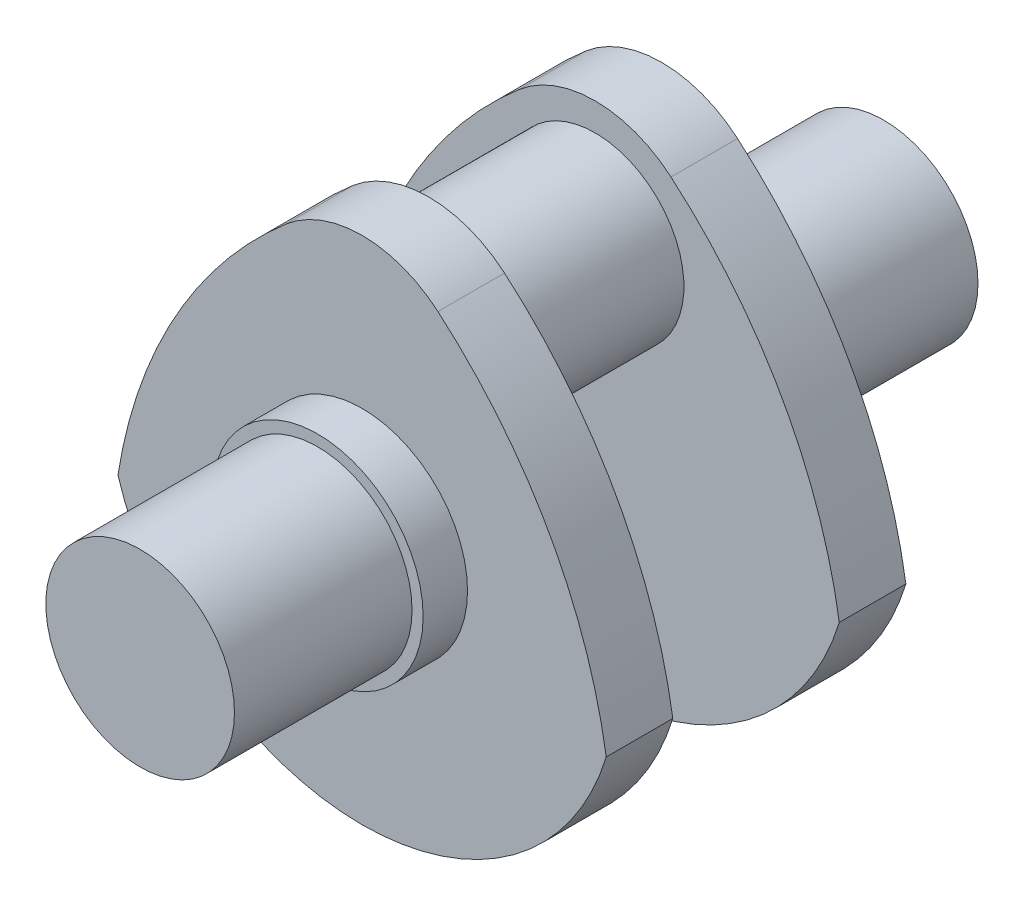
SolidWorks part; units mm, degrees
ref_plane "Front Plane" through (0, 0, 0) normal (0, 0, 1) x (1, 0, 0)
ref_plane "Top Plane" through (0, 0, 0) normal (0, 1, 0) x (1, 0, 0)
ref_plane "Right Plane" through (0, 0, 0) normal (1, 0, 0) x (0, 0, -1)
sketch "Sketch3" plane through (0, 0, 0) normal (0, 0, 1) x (1, 0, 0)
  circle A0 centre (0, 0) radius 17
  dimension "D1" = 34
extrude "Boss-Extrude1" add sketch "Sketch3" along normal blind 40
sketch "Sketch6" plane through (0, 0, 40) normal (0, 0, 1) x (1, 0, 0)
  circle A0 centre (0, 0) radius 19
extrude "Boss-Extrude2" add sketch "Sketch6" against normal blind 8
sketch "Sketch7" plane through (0, 0, 40) normal (0, 0, 1) x (1, 0, 0)
  arc A0 (-44, -13.4164) -> (44, -13.4164) centre (0, 0) ccw
  arc A1 (13.6681, 40.9431) -> (-13.6681, 40.9431) centre (0, 25) ccw
  arc A2 (-44, -13.4164) -> (-13.6681, 40.9431) centre (44.9095, -27.3845) cw
  arc A3 (44, -13.4164) -> (13.6681, 40.9431) centre (-44.9095, -27.3845) ccw
  dimension "D1" = 88
  dimension "D2" = 46
  dimension "D3" = 42
  dimension "D5" = 90
  dimension "D6" = 90
  dimension "D4" = 25
extrude "Boss-Extrude3" add sketch "Sketch7" along normal blind 12
sketch "Sketch8" plane through (0, 0, 52) normal (0, 0, 1) x (1, 0, 0)
  circle A0 centre (0, 25) radius 16
  dimension "D1" = 32
  dimension "D2" = 25
extrude "Boss-Extrude4" add sketch "Sketch8" along normal blind 15 contours A0
mirror "Mirror2" about plane through (0, 25, 67) normal (0, 0, 1) of bodies 104
